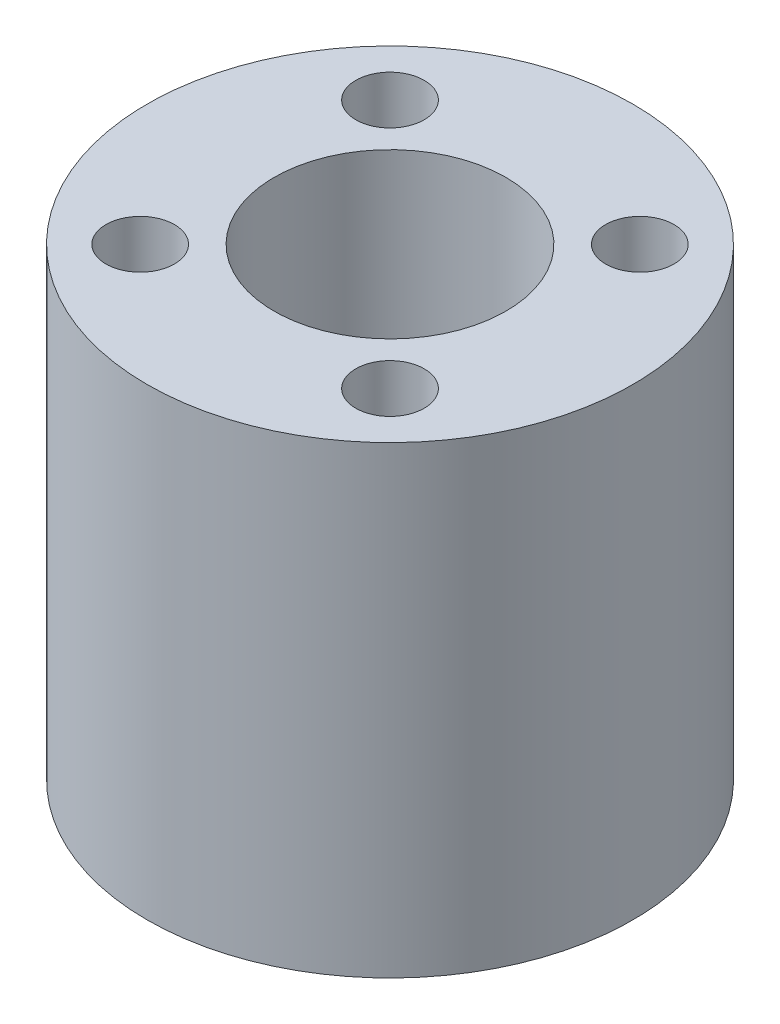
SolidWorks part; units mm, degrees
ref_plane "Alzado" through (0, 0, 0) normal (0, 0, 1) x (1, 0, 0)
ref_plane "Planta" through (0, 0, 0) normal (0, 1, 0) x (1, 0, 0)
ref_plane "Vista lateral" through (0, 0, 0) normal (1, 0, 0) x (0, 0, -1)
sketch "Croquis1" plane through (0, 0, 0) normal (0, 1, 0) x (1, 0, 0)
  line L0 (-8.3, -8.3) -> (8.3, 8.3) construction
  line L1 (-8.3, 8.3) -> (8.3, -8.3) construction
  circle A0 centre (0, 0) radius 5.25
  circle A1 centre (5.6569, 5.6569) radius 1.55
  circle A2 centre (-5.6569, 5.6569) radius 1.55
  circle A3 centre (-5.6569, -5.6569) radius 1.55
  circle A4 centre (5.6569, -5.6569) radius 1.55
  circle A5 centre (0, 0) radius 11
  dimension "D1" = 10.5
  dimension "D2" = 22
  dimension "D3" = 3.1
  dimension "D4" = 3.1
  dimension "D5" = 3.1
  dimension "D6" = 3.1
extrude "Saliente-Extruir1" add sketch "Croquis1" along normal blind 21
